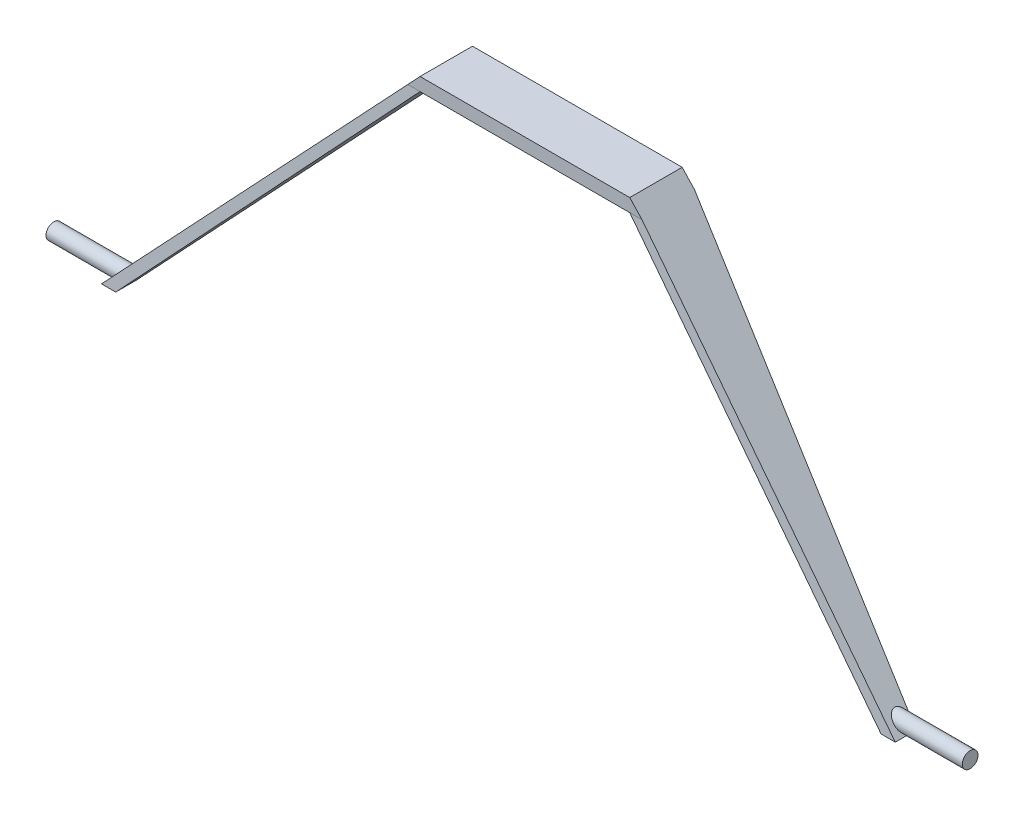
SolidWorks part; units mm, degrees
ref_plane "Front" through (0, 0, 0) normal (0, 0, 1) x (1, 0, 0)
ref_plane "Top" through (0, 0, 0) normal (0, 1, 0) x (1, 0, 0)
ref_plane "Right" through (0, 0, 0) normal (1, 0, 0) x (0, 0, -1)
sketch "Sketch12" plane through (0, 0, 0) normal (0, 0, 1) x (1, 0, 0)
  line L0 (-203.2, 241.3) -> (203.2, 241.3)
  line L1 (0, 241.3) -> (0, -425.45) construction
  line L2 (-203.2, 241.3) -> (-787.4717, -383.6692)
  line L3 (-787.4717, -383.6692) -> (-787.4717, -424.3092)
  line L4 (-787.4717, -424.3092) -> (-762.0717, -424.3092)
  line L5 (-762.0717, -424.3092) -> (-762.0717, -386.2092)
  line L6 (-762.0717, -386.2092) -> (-203.2, 215.9)
  line L7 (-203.2, 215.9) -> (203.2, 215.9)
  line L9 (762.0717, -386.2092) -> (203.2, 215.9)
  line L10 (762.0717, -424.3092) -> (762.0717, -386.2092)
  line L11 (787.4717, -424.3092) -> (762.0717, -424.3092)
  line L12 (787.4717, -383.6692) -> (787.4717, -424.3092)
  line L13 (203.2, 241.3) -> (787.4717, -383.6692)
  point P14 (0, 215.9)
  dimension "D1" = 666.75
  dimension "D2" = 40.64
  dimension "D3" = 25.4
  dimension "D4" = 38.1
extrude "Boss-Extrude6" add sketch "Sketch12" along normal blind 53.34 and the other way blind 101.6
sketch "Sketch13" plane through (787.4717, 0, 0) normal (1, 0, 0) x (0, 0, -1)
  line L0 (-53.34, -424.3092) -> (-53.34, -383.6692) construction
  line L1 (101.6, -424.3092) -> (-53.34, -424.3092) construction
  circle A0 centre (-34.29, -405.2592) radius 19.05
  dimension "D1" = 38.1
  dimension "D2" = 19.05
  dimension "D3" = 19.05
sketch "Sketch14" plane through (0, 0, 0) normal (1, 0, 0) x (0, 0, -1)
  line L0 (-53.34, 241.3) -> (0, 241.3) construction
  line L1 (101.6, 241.3) -> (-53.34, 241.3) construction
  line L2 (0, 241.3) -> (0, 215.9)
  line L5 (-53.34, -386.2092) -> (-15.24, -386.2092) construction
  line L6 (101.6, -386.2092) -> (-53.34, -386.2092) construction
  line L7 (0, 215.9) -> (-53.34, -386.2092)
  line L8 (-53.34, -386.2092) -> (-53.34, 241.3)
  line L9 (101.6, 215.9) -> (-15.24, -386.2092)
  line L10 (-15.24, -386.2092) -> (-15.24, -424.3092)
  line L11 (101.6, -424.3092) -> (-53.34, -424.3092) construction
  line L12 (-15.24, -424.3092) -> (101.6, -424.3092)
  line L13 (101.6, -424.3092) -> (101.6, 215.9)
  line L14 (-53.34, 241.3) -> (0, 241.3)
  dimension "D1" = 53.34
  dimension "D2" = 38.1
extrude "Cut-Extrude8" cut sketch "Sketch14" against normal up to surface and the other way up to surface up to face at (-495.3358, -71.1846, -24.13) other way up to face at (495.3358, -71.1846, -24.13)
ref_plane "Plane1" through (-762.0717, 0, 0) normal (-1, 0, 0) x (0, 0, 1)
sketch "Sketch15" plane through (-762.0717, 0, 0) normal (-1, 0, 0) x (0, 0, 1)
  line L0 (34.29, -405.2592) -> (34.29, -394.8452) construction
  line L1 (53.34, -386.2092) -> (53.34, -424.3092) construction
  circle A0 centre (34.29, -394.8452) radius 19.05
  dimension "D2" = 38.1
  dimension "D3" = 19.05
  dimension "D1" = 10.414
extrude "Boss-Extrude8" add sketch "Sketch15" along normal blind 127
mirror "Mirror2" about plane through (0, 0, 0) normal (1, 0, 0) of "Boss-Extrude8"
sketch "Sketch16" plane through (-762.0717, 0, 0) normal (-1, 0, 0) x (0, 0, 1)
  line L0 (15.24, -424.3092) -> (15.24, -394.8452) construction
  line L1 (15.24, -413.8952) -> (53.34, -413.8952)
  line L2 (15.24, -413.8952) -> (15.24, -424.3092)
  line L3 (15.24, -424.3092) -> (53.34, -424.3092)
  line L4 (53.34, -413.8952) -> (53.34, -424.3092)
extrude "Cut-Extrude9" cut sketch "Sketch16" along normal up to surface and the other way up to surface up to face at (-787.4717, -414.3397, 34.29) other way up to face at (787.4717, -414.3397, 34.29)
sketch "Sketch17" plane through (-762.0717, 0, 0) normal (-1, 0, 0) x (0, 0, 1)
  line L0 (23.7425, -345.5692) -> (23.7425, -342.5212) construction
  line L1 (23.7425, -345.5692) -> (23.7425, -348.8712) construction
  line L2 (7.9945, -348.8712) -> (23.2345, -348.8712) construction
  line L3 (-101.6, 215.9) -> (14.7471, -383.6692) construction
  circle A2 centre (23.7425, -348.8712) radius 15.24
  dimension "D2" = 3.302
  dimension "D3" = 30.48
  dimension "D4" = 15.24
  dimension "D1" = 3.048
  dimension "D5" = 0.508
extrude "Boss-Extrude9" add sketch "Sketch17" along normal blind 127 and the other way up to surface other way up to face at (-500.3522, -76.5504, -8.3447)
ref_plane "Plane2" through (759.5317, 0, 0) normal (-1, 0, 0) x (0, 0, 1)
sketch "Sketch18" plane through (759.5317, 0, 0) normal (-1, 0, 0) x (0, 0, 1)
  line L0 (23.6894, -345.2957) -> (23.6894, -342.5617) construction
  line L1 (23.6894, -345.2957) -> (23.6894, -348.5977) construction
  line L2 (7.9414, -348.5977) -> (23.1814, -348.5977) construction
  line L3 (-101.6, 215.9) -> (14.7471, -383.6692) construction
  circle A2 centre (23.6894, -348.5977) radius 15.24
  dimension "D2" = 3.302
  dimension "D1" = 30.48
  dimension "D3" = 15.24
  dimension "D4" = 0.508
extrude "Boss-Extrude10" add sketch "Sketch18" against normal blind 127 and the other way up to surface other way up to face at (500.3522, -76.5504, -8.3447)
sketch "Sketch19" plane through (759.5317, 0, 0) normal (-1, 0, 0) x (0, 0, 1)
  line L0 (53.34, -413.8952) -> (53.34, -364.1112)
  line L6 (53.34, -364.1112) -> (10.0154, -364.1112)
  line L8 (10.3111, -413.8952) -> (53.34, -413.8952)
  line L13 (9.7196, -413.8952) -> (10.3111, -413.8952)
  line L14 (10.0154, -364.1112) -> (9.7196, -413.8952)
extrude "Cut-Extrude10" cut sketch "Sketch19" against normal up to surface and the other way up to surface up to face at (889.0717, -394.8452, 53.34) other way up to face at (-889.0717, -394.8452, 53.34)
